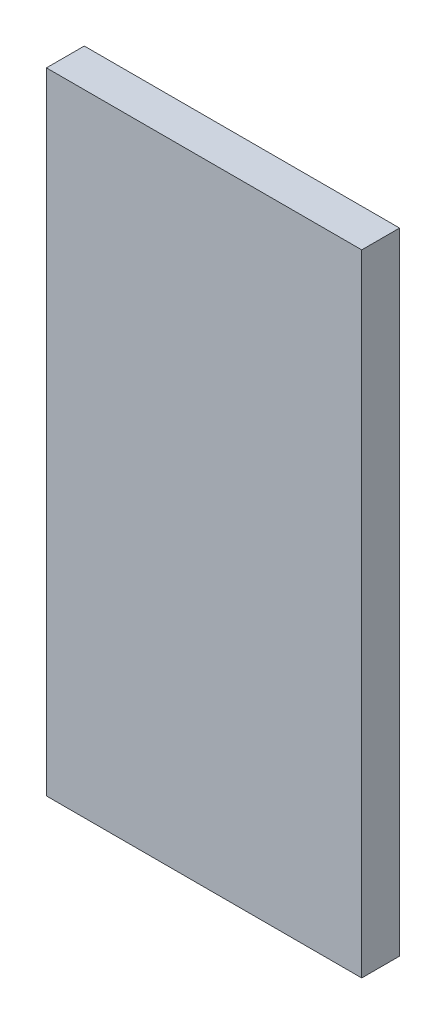
SolidWorks part; units mm, degrees
ref_plane "Ebene vorne" through (0, 0, 0) normal (0, 0, 1) x (1, 0, 0)
ref_plane "Ebene oben" through (0, 0, 0) normal (0, 1, 0) x (1, 0, 0)
ref_plane "Ebene rechts" through (0, 0, 0) normal (1, 0, 0) x (0, 0, -1)
sketch "Skizze1" plane through (0, 0, 0) normal (0, 0, 1) x (1, 0, 0)
  line L1 (-0.125, -0.25) -> (0.125, -0.25)
  line L2 (-0.125, -0.25) -> (-0.125, 0.25)
  line L3 (-0.125, 0.25) -> (0.125, 0.25)
  line L4 (0.125, -0.25) -> (0.125, 0.25)
  line L5 (-0.125, -0.25) -> (0.125, 0.25) construction
  line L6 (-0.125, 0.25) -> (0.125, -0.25) construction
  point P0 (0, 0)
  dimension "D1" = 0.5
  dimension "D2" = 0.25
extrude "Aufsatz-Linear austragen1" add sketch "Skizze1" along normal blind 0.03
sketch "Skizze2" plane through (0, 0.25, 0) normal (0, 1, 0) x (1, 0, 0)
  line L4 (0.125, 0) -> (-0.125, 0)
  line L5 (-0.125, 0) -> (-0.125, -0.03)
  line L6 (-0.125, -0.03) -> (0.125, -0.03)
  line L7 (0.125, -0.03) -> (0.125, 0)
  line L8 (0.125, 0) -> (-0.125, 0)
  line L9 (-0.125, 0) -> (-0.125, -0.03)
  line L10 (-0.125, -0.03) -> (0.125, -0.03)
  line L11 (0.125, -0.03) -> (0.125, 0)
  point P2 (0, -0.03)
  point P4 (0, 0)
  dimension "D1" = 0
ref_point "SWASI_Vision_Top_3"
ref_point "SWASI_Vision_Top_1"
ref_point "SWASI_Vision_Top_2"
ref_point "SWASI_Vision_Top_4"
sketch "Skizze3" plane through (0, -0.25, 0) normal (0, -1, 0) x (1, 0, 0)
  line L4 (-0.125, 0) -> (0.125, 0)
  line L5 (0.125, 0) -> (0.125, 0.03)
  line L6 (0.125, 0.03) -> (-0.125, 0.03)
  line L7 (-0.125, 0.03) -> (-0.125, 0)
  line L8 (-0.125, 0) -> (0.125, 0)
  line L9 (0.125, 0) -> (0.125, 0.03)
  line L10 (0.125, 0.03) -> (-0.125, 0.03)
  line L11 (-0.125, 0.03) -> (-0.125, 0)
  point P2 (0, 0.03)
  point P4 (0, 0)
  dimension "D1" = 0
ref_point "SWASI_Vision_Bottom_3"
ref_point "SWASI_Vision_Bottom_2"
ref_point "SWASI_Vision_Bottom_4"
ref_point "SWASI_Vision_Bottom_1"
ref_point "SWASI_Vision_Top_34"
ref_point "SWASI_Vision_Top_12"
ref_point "SWASI_Vision_Bottom_34"
ref_point "SWASI_Vision_Bottom_12"
